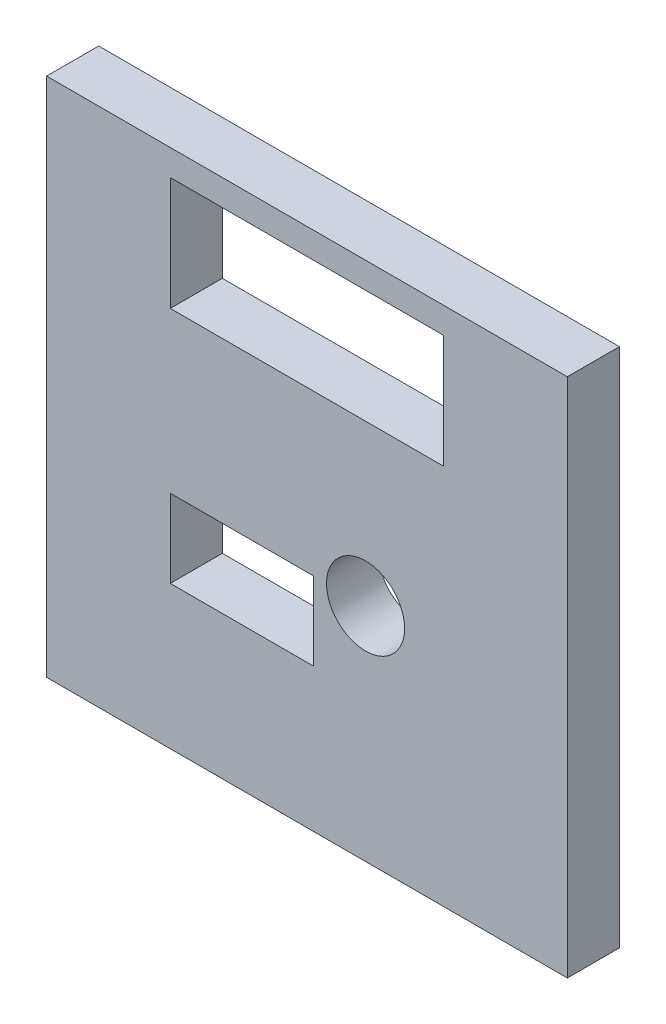
SolidWorks part; units mm, degrees
ref_plane "Front Plane" through (0, 0, 0) normal (0, 0, 1) x (1, 0, 0)
ref_plane "Top Plane" through (0, 0, 0) normal (0, 1, 0) x (1, 0, 0)
ref_plane "Right Plane" through (0, 0, 0) normal (1, 0, 0) x (0, 0, -1)
sketch "Sketch1" plane through (0, 0, 0) normal (0, 0, 1) x (1, 0, 0)
  line L1 (10, -10) -> (-10, -10)
  line L2 (10, -10) -> (10, 10)
  line L3 (10, 10) -> (-10, 10)
  line L4 (-10, -10) -> (-10, 10)
  line L5 (10, -10) -> (-10, 10) construction
  line L6 (10, 10) -> (-10, -10) construction
  point P0 (0, 0)
  dimension "D1" = 20
  dimension "D2" = 20
extrude "Boss-Extrude1" add sketch "Sketch1" along normal blind 2
sketch "Sketch2" plane through (0, 0, 2) normal (0, 0, 1) x (1, 0, 0)
  line L0 (0, 0) -> (0, 10) construction
  line L1 (10, 10) -> (-10, 10) construction
  line L2 (-10, -10) -> (10, -10) construction
  line L3 (5.25, -4.5) -> (-5.25, -4.5)
  line L4 (5.25, -4.5) -> (5.25, 9)
  line L5 (5.25, 9) -> (-5.25, 9)
  line L6 (-5.25, -4.5) -> (-5.25, 9)
  line L7 (5.25, -4.5) -> (-5.25, 9) construction
  line L8 (5.25, 9) -> (-5.25, -4.5) construction
  line L10 (5.25, 4.6464) -> (-5.25, 4.6464)
  line L11 (5.25, 4.6464) -> (5.25, 9)
  line L12 (5.25, 9) -> (-5.25, 9)
  line L13 (-5.25, 4.6464) -> (-5.25, 9)
  line L14 (5.25, 4.6464) -> (-5.25, 9) construction
  line L15 (5.25, 9) -> (-5.25, 4.6464) construction
  line L16 (0.25, -4.5) -> (-5.25, -4.5)
  line L17 (0.25, -4.5) -> (0.25, -1.5)
  line L18 (0.25, -1.5) -> (-5.25, -1.5)
  line L19 (-5.25, -4.5) -> (-5.25, -1.5)
  line L20 (0.25, -4.5) -> (-5.25, -1.5) construction
  line L21 (0.25, -1.5) -> (-5.25, -4.5) construction
  circle A0 centre (2.25, -1.5) radius 1.5
  point P5 (0, 2.25)
  point P12 (0, 6.8232)
  point P13 (-2.5, -3)
  dimension "D4" = 3
  dimension "D1" = 5.5
  dimension "D2" = 13.5
  dimension "D3" = 10.5
  dimension "D5" = 3
  dimension "D6" = 3
  dimension "D7" = 5.5
  dimension "D8" = 5.5
  dimension "D9" = 3
extrude "Cut-Extrude1" cut sketch "Sketch2" against normal blind 10 contours L10 L4 L5 L6 | L17 L18 L6 L16 | A0
